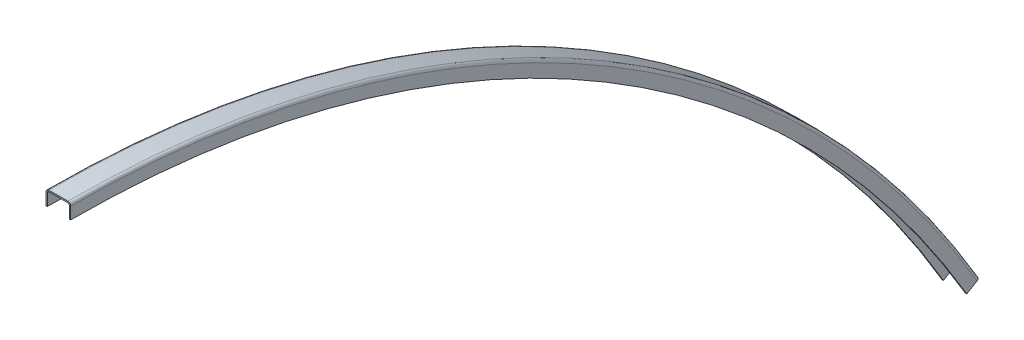
SolidWorks part; units mm, degrees
material "Galvanized Steel"
ref_plane "Front Plane" through (0, 0, 0) normal (0, 0, 1) x (1, 0, 0)
ref_plane "Top Plane" through (0, 0, 0) normal (0, 1, 0) x (1, 0, 0)
ref_plane "Right Plane" through (0, 0, 0) normal (1, 0, 0) x (0, 0, -1)
sketch "Sketch1" plane through (0, 0, 0) normal (0, 0, 1) x (1, 0, 0)
  line L0 (-23.2037, 37.9815) -> (-23.2037, 54.9815)
  line L1 (-19.2037, 58.9815) -> (7.7963, 58.9815)
  line L2 (11.7963, 54.9815) -> (11.7963, 37.9815)
  line L3 (11.7963, 37.9815) -> (9.7963, 37.9815)
  line L4 (9.7963, 37.9815) -> (9.7963, 54.9815)
  line L5 (7.7963, 56.9815) -> (-19.2037, 56.9815)
  line L6 (-21.2037, 54.9815) -> (-21.2037, 37.9815)
  line L7 (-21.2037, 37.9815) -> (-23.2037, 37.9815)
  line L8 (14.4794, -1435.5185) -> (-23.2037, -1435.5185) construction
  arc A0 (9.7963, 54.9815) -> (7.7963, 56.9815) centre (7.7963, 54.9815) ccw
  arc A1 (-21.2037, 54.9815) -> (-19.2037, 56.9815) centre (-19.2037, 54.9815) cw
  arc A2 (7.7963, 58.9815) -> (11.7963, 54.9815) centre (7.7963, 54.9815) cw
  arc A3 (-23.2037, 54.9815) -> (-19.2037, 58.9815) centre (-19.2037, 54.9815) cw
  point P14 (11.7963, 58.9815)
  point P17 (-23.2037, 58.9815)
  dimension "D7" = 2
  dimension "D8" = 4
  dimension "D1" = 35
  dimension "D2" = 21
  dimension "D3" = 21
  dimension "D4" = 1494.5
  dimension "D6" = 2
revolve "Revolve1" add sketch "Sketch1" angle 59.5 about L8
